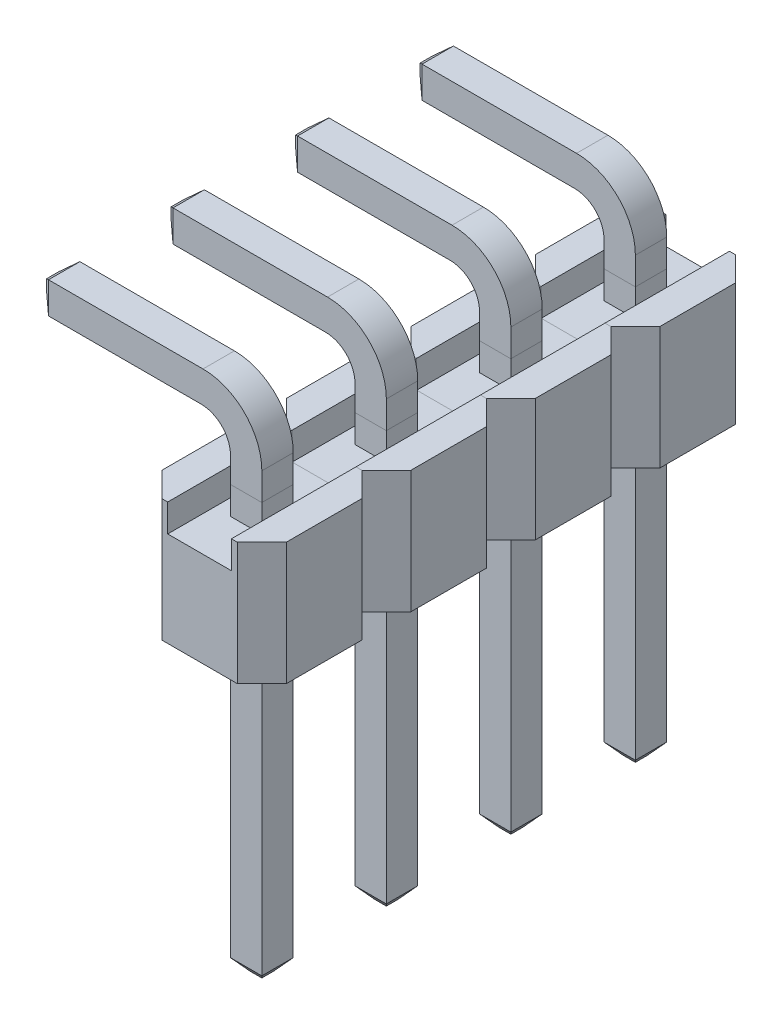
SolidWorks part; units mm, degrees
ref_plane "Front Plane" through (0, 0, 0) normal (0, 0, 1) x (1, 0, 0)
ref_plane "Top Plane" through (0, 0, 0) normal (0, 1, 0) x (1, 0, 0)
ref_plane "Right Plane" through (0, 0, 0) normal (1, 0, 0) x (0, 0, -1)
sketch "Эскиз1" plane through (0, 0, 0) normal (0, 1, 0) x (1, 0, 0)
  line L1 (1.27, 1.27) -> (-1.27, 1.27)
  line L2 (1.27, 1.27) -> (1.27, -1.27)
  line L3 (1.27, -1.27) -> (-1.27, -1.27)
  line L4 (-1.27, 1.27) -> (-1.27, -1.27)
  line L5 (1.27, 1.27) -> (-1.27, -1.27) construction
  line L6 (1.27, -1.27) -> (-1.27, 1.27) construction
  point P0 (0, 0)
  dimension "D1" = 2.54
  dimension "D2" = 2.54
extrude "Body" add sketch "Эскиз1" along normal blind 2.5
sketch "Эскиз3" plane through (0, 0, 1.27) normal (0, 0, 1) x (1, 0, 0)
  line L0 (-1.27, 2.5) -> (1.27, 2.5) construction
  line L1 (-0.65, 2.5) -> (0.65, 2.5)
  line L2 (-0.65, 2.5) -> (-0.65, 1.9351)
  line L3 (-0.65, 1.9351) -> (0.65, 1.9351)
  line L4 (0.65, 2.5) -> (0.65, 1.9351)
  line L5 (0, 0) -> (0, 1.3698) construction
  dimension "D1" = 1.3
extrude "Groove" cut sketch "Эскиз3" against normal blind 3
chamfer "Chamfer" distance 0.5 angle 45 4 edges at (-1.27, 1.25, -1.27) (-1.27, 1.25, 1.27) (1.27, 1.25, 1.27) (1.27, 1.25, -1.27)
sketch "Эскиз2" plane through (0, 2.5, 0) normal (0, 1, 0) x (1, 0, 0)
  line L1 (0.32, 0.32) -> (-0.32, 0.32)
  line L2 (0.32, 0.32) -> (0.32, -0.32)
  line L3 (0.32, -0.32) -> (-0.32, -0.32)
  line L4 (-0.32, 0.32) -> (-0.32, -0.32)
  line L5 (0.32, 0.32) -> (-0.32, -0.32) construction
  line L6 (0.32, -0.32) -> (-0.32, 0.32) construction
  point P0 (0, 0)
  dimension "D1" = 0.64
  dimension "D2" = 0.64
extrude "Pin" add sketch "Эскиз2" against normal blind 8.6
chamfer "PinChamfer" distance 0.2 angle 50 4 edges at (0, -6.1, -0.32) (0.32, -6.1, 0) (0, -6.1, 0.32) (-0.32, -6.1, 0)
sketch "Scetch" plane through (0, 0, -0.32) normal (0, 0, -1) x (-1, 0, 0)
  line L0 (0.88, 4.26) -> (4.27, 4.26)
  line L1 (4.27, 4.26) -> (4.27, 3.62)
  line L2 (4.27, 3.62) -> (0.92, 3.62)
  line L3 (0.32, 3.02) -> (0.32, 2.5)
  line L4 (0.32, 2.5) -> (-0.32, 2.5)
  line L5 (-0.32, 2.5) -> (-0.32, 3.06)
  line L6 (-0.32, 1.9351) -> (-0.32, 2.5) construction
  line L7 (0.12, -6.1) -> (-0.12, -6.1) construction
  line L8 (1.27, 2.5) -> (1.27, 0) construction
  arc A0 (0.92, 3.62) -> (0.32, 3.02) centre (0.92, 3.02) ccw
  arc A1 (-0.32, 3.06) -> (0.88, 4.26) centre (0.88, 3.06) cw
  dimension "D3" = 0.6
  dimension "D4" = 1.2
  dimension "D1" = 0.64
  dimension "D2" = 10.36
  dimension "D5" = 3
extrude "RPin" add sketch "Scetch" against normal up to surface (0.64 mm away) separate body up to face at (0, 2.2176, 0.32)
chamfer "RPinChamfer" distance 0.2 angle 50 4 edges at (-4.27, 3.94, -0.32) (-4.27, 4.26, 0) (-4.27, 3.94, 0.32) (-4.27, 3.62, 0)
sketch "Sketch3" [suppressed] plane through (0, 0, 0) normal (0, 0, 1) x (1, 0, 0)
  line L0 (-0.77, 0) -> (0.77, 0) construction
  line L1 (-0.32, 0) -> (0.32, 0)
  line L2 (-0.32, 0) -> (-0.32, -0.5)
  line L4 (0.32, 0) -> (0.32, -0.46)
  line L5 (-0.65, 1.9351) -> (0.65, 1.9351) construction
  line L6 (0.32, 1.9351) -> (-0.32, 1.9351)
  line L7 (0.32, 1.9351) -> (0.32, 5.5)
  line L8 (-0.32, 5.5) -> (0.32, 5.5)
  line L9 (-0.32, 1.9351) -> (-0.32, 5.5)
  line L10 (-1.27, 2.5) -> (-0.77, 2.5) construction
  line L12 (0.68, -1.5) -> (7.18, -1.5)
  line L14 (0.72, -0.86) -> (7.18, -0.86)
  line L15 (7.18, -1.5) -> (7.18, -0.86)
  arc A0 (-0.32, -0.5) -> (0.68, -1.5) centre (0.68, -0.5) ccw
  arc A1 (0.32, -0.46) -> (0.72, -0.86) centre (0.72, -0.46) ccw
  point P15 (0, 0)
  point P17 (0, 1.9351)
  dimension "D4" = 1
  dimension "D5" = 0.4
  dimension "D1" = 0.64
  dimension "D2" = 0.64
  dimension "D3" = 3
  dimension "D6" = 0.64
  dimension "D7" = 1.5
  dimension "D8" = 7.5
extrude "Boss-Extrude1" [suppressed] add sketch "Sketch3" along normal mid plane 0.64
chamfer "Chamfer1" [suppressed] distance 0.2 angle 50
pattern_linear "LPattern2" count 4 spacing 2.54 along (0, 0, 1) of "Body"
pattern_linear "LPattern1" [suppressed] count 10 spacing 2.54
